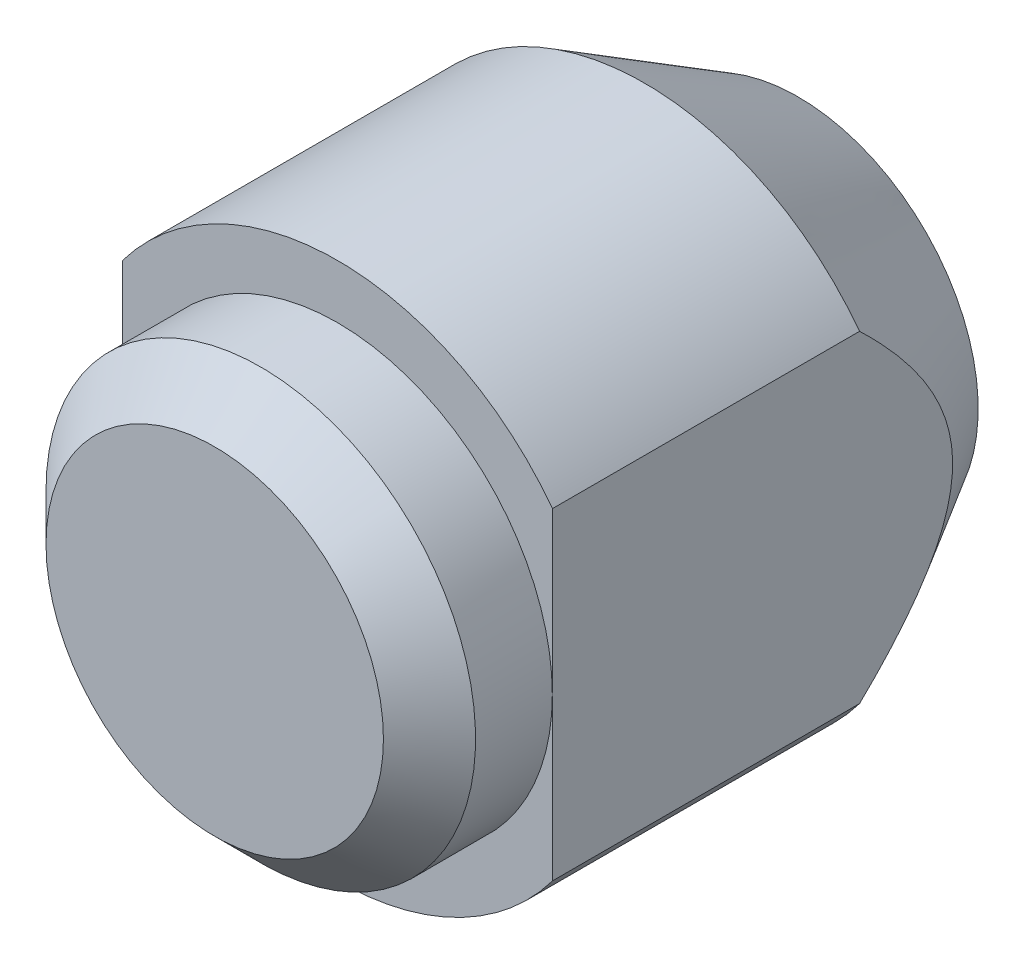
SolidWorks part; units mm, degrees
ref_plane "前视基准面" through (0, 0, 0) normal (0, 0, 1) x (1, 0, 0)
ref_plane "上视基准面" through (0, 0, 0) normal (0, 1, 0) x (1, 0, 0)
ref_plane "右视基准面" through (0, 0, 0) normal (1, 0, 0) x (0, 0, -1)
other "Configuration Table"
sketch "草图1" plane through (0, 0, 0) normal (0, 0, 1) x (1, 0, 0)
  circle A0 centre (28.5841, -59.6905) radius 1.75
  dimension "D1" = 3.5
extrude "凸台-拉伸1" add sketch "草图1" along normal blind 2
sketch "草图2" plane through (0, 0, 2) normal (0, 0, 1) x (1, 0, 0)
  circle A0 centre (28.5841, -59.6905) radius 1.3989
  dimension "D1" = 2.7978
extrude "凸台-拉伸2" add sketch "草图2" along normal blind 0.8
chamfer "倒角1" distance 0.3 angle 45 1 edges at (29.983, -59.6905, 2.8)
sketch "草图3" plane through (0, 0, 0) normal (0, 0, -1) x (-1, 0, 0)
  circle A1 centre (-28.5841, -59.6905) radius 1.75
  circle A2 centre (-28.5841, -59.6905) radius 1.75
  dimension "D1" = 0
extrude "凸台-拉伸3" add sketch "草图3" along normal blind 1 draft 30
sketch "草图4" plane through (0, 0, -1) normal (0, 0, -1) x (-1, 0, 0)
  line L1 (-25.6533, -62.0346) -> (-27.1841, -62.0346)
  line L2 (-25.6533, -62.0346) -> (-25.6533, -57.5795)
  line L3 (-25.6533, -57.5795) -> (-27.1841, -57.5795)
  line L4 (-27.1841, -62.0346) -> (-27.1841, -57.5795)
  line L5 (-29.9841, -62.0346) -> (-31.5025, -62.0346)
  line L6 (-29.9841, -62.0346) -> (-29.9841, -57.5795)
  line L7 (-29.9841, -57.5795) -> (-31.5025, -57.5795)
  line L8 (-31.5025, -62.0346) -> (-31.5025, -57.5795)
  circle A0 centre (-28.5841, -59.6905) radius 1.1726 construction
  circle A1 centre (-28.5841, -59.6905) radius 1.1726 construction
  point P11 (0, 0)
  dimension "D1" = 1.4
  dimension "D2" = 1.4
extrude "切除-拉伸2" cut sketch "草图4" against normal blind 3
